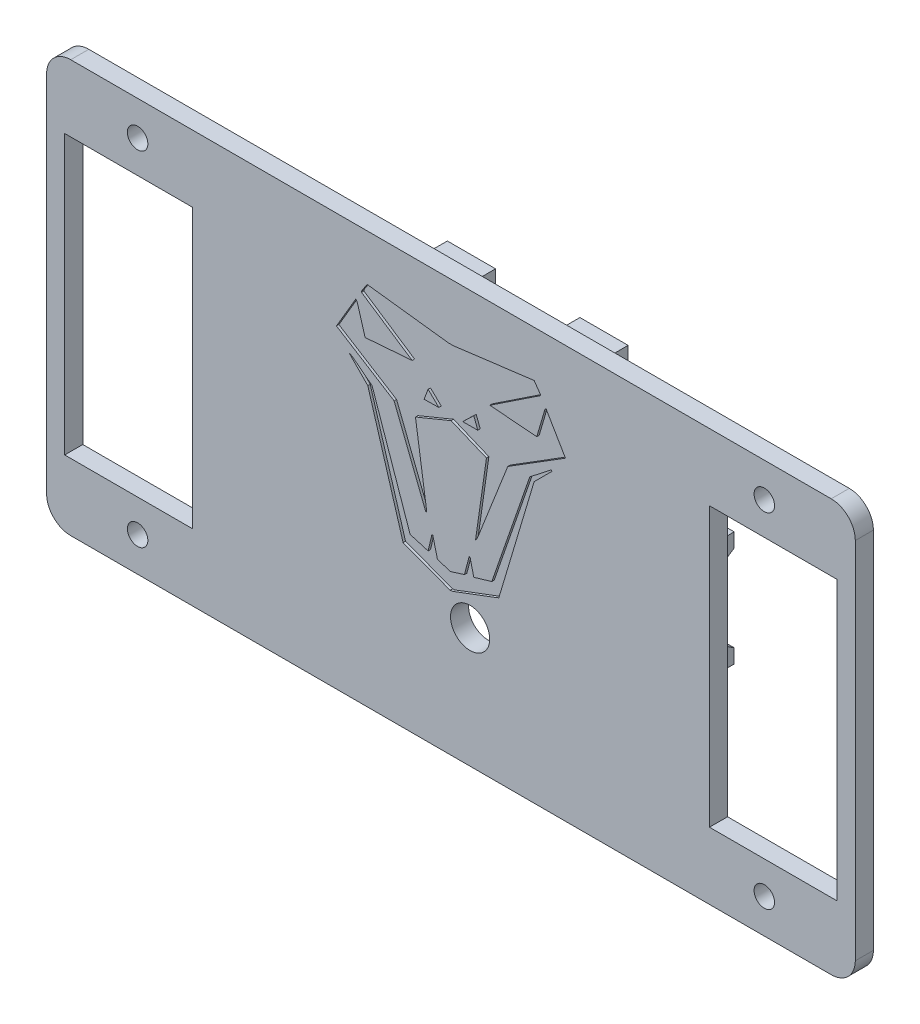
SolidWorks part; units mm, degrees
material "Overture Super PLA Plus"
ref_plane "Front Plane" through (0, 0, 0) normal (0, 0, 1) x (1, 0, 0)
ref_plane "Top Plane" through (0, 0, 0) normal (0, 1, 0) x (1, 0, 0)
ref_plane "Right Plane" through (0, 0, 0) normal (1, 0, 0) x (0, 0, -1)
sketch "Lid_Footprint" plane through (0, 0, 0) normal (0, 0, 1) x (1, 0, 0)
  line L1 (-67.1, -34.2) -> (67.1, -34.2)
  line L2 (-67.1, -34.2) -> (-67.1, 34.2)
  line L3 (-67.1, 34.2) -> (67.1, 34.2)
  line L4 (67.1, -34.2) -> (67.1, 34.2)
  dimension "R1_Width" = 134.2
  dimension "R1_Length" = 68.4
  dimension "R1_X" = 67.1
  dimension "R1_Y" = 34.2
extrude "Lid_Plate" add sketch "Lid_Footprint" along normal blind 3 from offset 32.5
sketch "Wheel_Well_Profile" plane through (0, 0, 0) normal (0, 0, 1) x (1, 0, 0)
  line L1 (42.9, -23.1) -> (64.1, -23.1)
  line L2 (42.9, -23.1) -> (42.9, 23.1)
  line L3 (42.9, 23.1) -> (64.1, 23.1)
  line L4 (64.1, -23.1) -> (64.1, 23.1)
  line L6 (-64.1, -23.1) -> (-42.9, -23.1)
  line L7 (-64.1, -23.1) -> (-64.1, 23.1)
  line L8 (-64.1, 23.1) -> (-42.9, 23.1)
  line L9 (-42.9, -23.1) -> (-42.9, 23.1)
  dimension "R1_Width" = 21.2
  dimension "R1_Length" = 46.2
  dimension "R1_X" = 42.9
  dimension "R1_Y" = 23.1
  dimension "R2_Width" = 21.2
  dimension "R2_Length" = 46.2
  dimension "R2_X" = 64.1
  dimension "R2_Y" = 23.1
extrude "Wheel_Clearance_Windows" cut sketch "Wheel_Well_Profile" against normal blind 5 from offset 36
sketch "Lid_Rib_Profile" plane through (0, 0, 0) normal (0, 0, 1) x (1, 0, 0)
  line L1 (-39, -8) -> (39, -8)
  line L2 (-39, -8) -> (-39, -5.5)
  line L3 (-39, -5.5) -> (39, -5.5)
  line L4 (39, -8) -> (39, -5.5)
  line L6 (-39, 5.5) -> (39, 5.5)
  line L7 (-39, 5.5) -> (-39, 8)
  line L8 (-39, 8) -> (39, 8)
  line L9 (39, 5.5) -> (39, 8)
  dimension "R1_Width" = 78
  dimension "R1_Length" = 2.5
  dimension "R1_X" = 39
  dimension "R1_Y" = 8
  dimension "R2_Width" = 78
  dimension "R2_Length" = 2.5
  dimension "R2_X" = 39
  dimension "R2_Y" = 5.5
extrude "Lid_Stiffening_Ribs" add sketch "Lid_Rib_Profile" along normal blind 3 from offset 29.5
sketch "Upper_Motor_Clamp_Profile" plane through (0, 0, 0) normal (0, 0, 1) x (1, 0, 0)
  line L1 (-35.1, -9.5) -> (-25.1, -9.5)
  line L2 (-35.1, -9.5) -> (-35.1, 9.5)
  line L3 (-35.1, 9.5) -> (-25.1, 9.5)
  line L4 (-25.1, -9.5) -> (-25.1, 9.5)
  line L6 (25.1, -9.5) -> (35.1, -9.5)
  line L7 (25.1, -9.5) -> (25.1, 9.5)
  line L8 (25.1, 9.5) -> (35.1, 9.5)
  line L9 (35.1, -9.5) -> (35.1, 9.5)
  dimension "R1_Width" = 10
  dimension "R1_Length" = 19
  dimension "R1_X" = 35.1
  dimension "R1_Y" = 9.5
  dimension "R2_Width" = 10
  dimension "R2_Length" = 19
  dimension "R2_X" = 25.1
  dimension "R2_Y" = 9.5
extrude "Lid_Motor_Clamp_Blocks" add sketch "Upper_Motor_Clamp_Profile" along normal blind 8.9 from offset 23.6
sketch "Upper_Clamp_Radius_Profile" plane through (0, 0, 0) normal (1, 0, 0) x (0, 0, -1)
  circle A0 centre (-19.6, 0) radius 8.2
  dimension "C1_Diameter" = 16.4
  dimension "Motor_Axis_Height" = 19.6
extrude "Upper_Motor_Clamp_Seats_R8p2" cut sketch "Upper_Clamp_Radius_Profile" against normal blind 72 from offset 36
sketch "Lid_Registration_Profile" plane through (0, 0, 0) normal (0, 0, 1) x (1, 0, 0)
  line L1 (-32.5, 30) -> (-0.5, 30)
  line L2 (-32.5, 30) -> (-32.5, 30.9)
  line L3 (-32.5, 30.9) -> (-0.5, 30.9)
  line L4 (-0.5, 30) -> (-0.5, 30.9)
  line L6 (0.5, 30) -> (32.5, 30)
  line L7 (0.5, 30) -> (0.5, 30.9)
  line L8 (0.5, 30.9) -> (32.5, 30.9)
  line L9 (32.5, 30) -> (32.5, 30.9)
  line L11 (-32.5, -30.9) -> (-0.5, -30.9)
  line L12 (-32.5, -30.9) -> (-32.5, -30)
  line L13 (-32.5, -30) -> (-0.5, -30)
  line L14 (-0.5, -30.9) -> (-0.5, -30)
  line L16 (0.5, -30.9) -> (32.5, -30.9)
  line L17 (0.5, -30.9) -> (0.5, -30)
  line L18 (0.5, -30) -> (32.5, -30)
  line L19 (32.5, -30.9) -> (32.5, -30)
  dimension "R1_Width" = 32
  dimension "R1_Length" = 0.9
  dimension "R1_X" = 32.5
  dimension "R1_Y" = 30
  dimension "R2_Width" = 32
  dimension "R2_Length" = 0.9
  dimension "R2_X" = 0.5
  dimension "R2_Y" = 30
  dimension "R3_Width" = 32
  dimension "R3_Length" = 0.9
  dimension "R3_X" = 32.5
  dimension "R3_Y" = 30.9
  dimension "R4_Width" = 32
  dimension "R4_Length" = 0.9
  dimension "R4_X" = 0.5
  dimension "R4_Y" = 30.9
extrude "Registration_Tabs" add sketch "Lid_Registration_Profile" along normal blind 1.5 from offset 31
sketch "Battery_Upper_Stop_Profile" plane through (0, 0, 0) normal (0, 0, 1) x (1, 0, 0)
  line L1 (-15, 17) -> (-7, 17)
  line L2 (-15, 17) -> (-15, 25)
  line L3 (-15, 25) -> (-7, 25)
  line L4 (-7, 17) -> (-7, 25)
  line L6 (7, 17) -> (15, 17)
  line L7 (7, 17) -> (7, 25)
  line L8 (7, 25) -> (15, 25)
  line L9 (15, 17) -> (15, 25)
  dimension "R1_Width" = 8
  dimension "R1_Length" = 8
  dimension "R1_X" = 15
  dimension "R1_Y" = 17
  dimension "R2_Width" = 8
  dimension "R2_Length" = 8
  dimension "R2_X" = 7
  dimension "R2_Y" = 17
extrude "Battery_Soft_Pad_Stops" add sketch "Battery_Upper_Stop_Profile" along normal blind 11.4 from offset 21.1
sketch "Lid_M3_Clearance_Profile" plane through (0, 0, 0) normal (0, 0, 1) x (1, 0, 0)
  circle A0 centre (-52, -28.5) radius 1.7
  circle A1 centre (-52, 28.5) radius 1.7
  circle A2 centre (52, -28.5) radius 1.7
  circle A3 centre (52, 28.5) radius 1.7
  dimension "C1_Diameter" = 3.4
  dimension "C2_Diameter" = 3.4
  dimension "C3_Diameter" = 3.4
  dimension "C4_Diameter" = 3.4
extrude "Lid_M3_Clearance_Holes" cut sketch "Lid_M3_Clearance_Profile" against normal blind 5 from offset 36
sketch "Switch_Retention_Rail_Profile" plane through (0, 0, 0) normal (0, 0, 1) x (1, 0, 0)
  line L1 (-11.5, -18.5) -> (-9.8, -18.5)
  line L2 (-11.5, -18.5) -> (-11.5, -10.2)
  line L3 (-11.5, -10.2) -> (-9.8, -10.2)
  line L4 (-9.8, -18.5) -> (-9.8, -10.2)
  line L6 (9.8, -18.5) -> (11.5, -18.5)
  line L7 (9.8, -18.5) -> (9.8, -10.2)
  line L8 (9.8, -10.2) -> (11.5, -10.2)
  line L9 (11.5, -18.5) -> (11.5, -10.2)
  dimension "R1_Width" = 1.7
  dimension "R1_Length" = 8.3
  dimension "R1_X" = 11.5
  dimension "R1_Y" = 18.5
  dimension "R2_Width" = 1.7
  dimension "R2_Length" = 8.3
  dimension "R2_X" = 9.8
  dimension "R2_Y" = 18.5
extrude "Switch_Retention_Rails" add sketch "Switch_Retention_Rail_Profile" along normal blind 14.1 from offset 18.4
sketch "Switch_Retention_Ledge_Profile" plane through (0, 0, 0) normal (0, 0, 1) x (1, 0, 0)
  line L1 (-11.5, -18.5) -> (-8.8, -18.5)
  line L2 (-11.5, -18.5) -> (-11.5, -10.2)
  line L3 (-11.5, -10.2) -> (-8.8, -10.2)
  line L4 (-8.8, -18.5) -> (-8.8, -10.2)
  line L6 (8.8, -18.5) -> (11.5, -18.5)
  line L7 (8.8, -18.5) -> (8.8, -10.2)
  line L8 (8.8, -10.2) -> (11.5, -10.2)
  line L9 (11.5, -18.5) -> (11.5, -10.2)
  dimension "R1_Width" = 2.7
  dimension "R1_Length" = 8.3
  dimension "R1_X" = 11.5
  dimension "R1_Y" = 18.5
  dimension "R2_Width" = 2.7
  dimension "R2_Length" = 8.3
  dimension "R2_X" = 8.8
  dimension "R2_Y" = 18.5
extrude "Switch_Retention_Ledges" add sketch "Switch_Retention_Ledge_Profile" along normal blind 1 from offset 17.4
sketch "Switch_Tool_Access_Profile" plane through (0, 0, 0) normal (0, 0, 1) x (1, 0, 0)
  circle A0 centre (3.175, -14.325) radius 3.25
  dimension "C1_Diameter" = 6.5
extrude "Switch_Tool_Access" cut sketch "Switch_Tool_Access_Profile" against normal blind 5 from offset 36
fillet "Lid_Outer_Corners_R4" radius 4 4 edges at (-67.1, 34.2, 34) (67.1, 34.2, 34) (67.1, -34.2, 34) (-67.1, -34.2, 34)
sketch "Snake_Logo_Native_Profile" plane through (0, 0, 0) normal (0, 0, 1) x (1, 0, 0)
  line L0 (13.8006, 26.5575) -> (14.8515, 25.064)
  line L1 (14.8515, 25.064) -> (14.8515, 24.8981)
  line L2 (14.8515, 24.8981) -> (6.444, 19.3115)
  line L3 (6.444, 19.3115) -> (14.2431, 18.7031)
  line L4 (14.2431, 18.7031) -> (15.46, 22.8515)
  line L5 (15.46, 22.8515) -> (15.6259, 23.3493)
  line L6 (15.6259, 23.3493) -> (15.7918, 23.46)
  line L7 (15.7918, 23.46) -> (19, 17.984)
  line L8 (19, 17.984) -> (9.4309, 12.0102)
  line L9 (9.4309, 12.0102) -> (4.3974, -0.7671)
  line L10 (4.3974, -0.7671) -> (4.0655, -1.3202)
  line L11 (4.0655, -1.3202) -> (5.8908, 11.4571)
  line L12 (5.8908, 11.4571) -> (0.0277, 13.8908)
  line L13 (0.0277, 13.8908) -> (-5.8908, 11.4571)
  line L14 (-5.8908, 11.4571) -> (-4.0655, -0.8777)
  line L15 (-4.0655, -0.8777) -> (-4.0655, -1.2649)
  line L16 (-4.0655, -1.2649) -> (-4.1761, -1.3202)
  line L17 (-4.1761, -1.3202) -> (-9.4309, 12.0102)
  line L18 (-9.4309, 12.0102) -> (-19, 17.984)
  line L19 (-19, 17.984) -> (-15.7918, 23.46)
  line L20 (-15.7918, 23.46) -> (-15.5706, 23.1834)
  line L21 (-15.5706, 23.1834) -> (-14.2431, 18.7031)
  line L22 (-14.2431, 18.7031) -> (-6.444, 19.3115)
  line L23 (-6.444, 19.3115) -> (-14.8515, 24.8981)
  line L24 (-14.8515, 24.8981) -> (-14.8515, 25.064)
  line L25 (-14.8515, 25.064) -> (-13.9112, 26.5022)
  line L26 (-13.9112, 26.5022) -> (-0.4148, 24.8428)
  line L27 (-0.4148, 24.8428) -> (0.4148, 24.8428)
  line L28 (0.4148, 24.8428) -> (13.8006, 26.5575)
  line L29 (-16.8428, 15.1077) -> (-16.5662, 15.0524)
  line L30 (-16.5662, 15.0524) -> (-16.6215, 14.9418)
  line L31 (-16.6215, 14.9418) -> (-16.5109, 14.9971)
  line L32 (-16.5109, 14.9971) -> (-15.9025, 14.5546)
  line L33 (-15.9025, 14.5546) -> (-13.1368, 12.3974)
  line L34 (-13.1368, 12.3974) -> (-13.0262, 12.1761)
  line L35 (-13.0262, 12.1761) -> (-6.7758, -5.8559)
  line L36 (-6.7758, -5.8559) -> (-3.7889, -6.7409)
  line L37 (-3.7889, -6.7409) -> (-3.1805, -4.1412)
  line L38 (-3.1805, -4.1412) -> (-3.0146, -4.0859)
  line L39 (-3.0146, -4.0859) -> (-2.2402, -7.1834)
  line L40 (-2.2402, -7.1834) -> (-0.083, -7.8472)
  line L41 (-0.083, -7.8472) -> (2.2402, -7.1281)
  line L42 (2.2402, -7.1281) -> (3.0146, -4.1412)
  line L43 (3.0146, -4.1412) -> (3.1805, -4.1965)
  line L44 (3.1805, -4.1965) -> (3.7889, -6.7409)
  line L45 (3.7889, -6.7409) -> (6.7758, -5.8559)
  line L46 (6.7758, -5.8559) -> (13.0815, 12.3421)
  line L47 (13.0815, 12.3421) -> (16.6215, 15.1077)
  line L48 (16.6215, 15.1077) -> (16.7875, 14.9971)
  line L49 (16.7875, 14.9971) -> (13.8006, 12.0102)
  line L50 (13.8006, 12.0102) -> (7.9374, -7.6259)
  line L51 (7.9374, -7.6259) -> (0.3042, -10.5022)
  line L52 (0.3042, -10.5022) -> (-0.1383, -10.5575)
  line L53 (-0.1383, -10.5575) -> (-7.9374, -7.6259)
  line L54 (-7.9374, -7.6259) -> (-13.8006, 12.0102)
  line L55 (-13.8006, 12.0102) -> (-16.8428, 15.1077)
  line L56 (-4.4527, 14.7205) -> (-2.0189, 14.7758)
  line L57 (-2.0189, 14.7758) -> (-3.7889, 16.4905)
  line L58 (-3.7889, 16.4905) -> (-4.4527, 14.7205)
  line L59 (1.9636, 14.7205) -> (4.4527, 14.7205)
  line L60 (4.4527, 14.7205) -> (3.7889, 16.4905)
  line L61 (3.7889, 16.4905) -> (1.9636, 14.7205)
extrude "Snake_Logo_Engraved" cut sketch "Snake_Logo_Native_Profile" against normal blind 0.4 from offset 35.5
equation "\"Overall_Width\"= 134.2mm"
equation "\"Overall_Length\"= 68.4mm"
equation "\"Wall\"= 3mm"
equation "\"Floor\"= 2.6mm"
equation "\"Case_Height\"= 32.5mm"
equation "\"Lid_Thickness\"= 3mm"
equation "\"Wheel_Diameter\"= 43.2mm"
equation "\"Wheel_Width\"= 14mm"
equation "\"Wheel_Bay_Inner_X\"= 42.9mm"
equation "\"Wheel_Radial_Clearance\"= 1.5mm"
equation "\"Wheel_Bay_Half_Length\"= \"Wheel_Diameter\"/2+\"Wheel_Radial_Clearance\""
equation "\"Ground_Clearance\"= 2mm"
equation "\"Motor_Axis_Z\"= \"Wheel_Diameter\"/2-\"Ground_Clearance\""
equation "\"Motor_Face_X\"= 38.1mm"
equation "\"Motor_Clamp_Radius\"= 8.2mm"
equation "\"Screw_Clearance\"= 3.4mm"
equation "\"Nut_AF_Clearance\"= 5.7mm"
equation "\"Engraving_Depth\"= 0.4mm"
equation "\"Hub_Offset_Min_Allowed\"= \"Wheel_Bay_Inner_X\"+1mm-\"Motor_Face_X\""
equation "\"Hub_Offset_Max_Allowed\"= \"Overall_Width\"/2-\"Wall\"-1mm-\"Wheel_Width\"-\"Motor_Face_X\""
equation "\"R1_Width@Lid_Footprint\" = \"Overall_Width\""
equation "\"R1_Length@Lid_Footprint\" = \"Overall_Length\""
equation "\"R1_X@Lid_Footprint\" = \"Overall_Width\"/2"
equation "\"R1_Y@Lid_Footprint\" = \"Overall_Length\"/2"
equation "\"D1@Lid_Plate\" = \"Lid_Thickness\""
equation "\"R1_Width@Wheel_Well_Profile\" = \"Overall_Width\"/2-\"Wall\"-\"Wheel_Bay_Inner_X\""
equation "\"R1_Length@Wheel_Well_Profile\" = 2*\"Wheel_Bay_Half_Length\""
equation "\"R1_X@Wheel_Well_Profile\" = \"Wheel_Bay_Inner_X\""
equation "\"R1_Y@Wheel_Well_Profile\" = \"Wheel_Bay_Half_Length\""
equation "\"R2_Width@Wheel_Well_Profile\" = \"Overall_Width\"/2-\"Wall\"-\"Wheel_Bay_Inner_X\""
equation "\"R2_Length@Wheel_Well_Profile\" = 2*\"Wheel_Bay_Half_Length\""
equation "\"R2_X@Wheel_Well_Profile\" = \"Overall_Width\"/2-\"Wall\""
equation "\"R2_Y@Wheel_Well_Profile\" = \"Wheel_Bay_Half_Length\""
equation "\"C1_Diameter@Upper_Clamp_Radius_Profile\" = 2*\"Motor_Clamp_Radius\""
equation "\"C1_Diameter@Lid_M3_Clearance_Profile\" = \"Screw_Clearance\""
equation "\"C2_Diameter@Lid_M3_Clearance_Profile\" = \"Screw_Clearance\""
equation "\"C3_Diameter@Lid_M3_Clearance_Profile\" = \"Screw_Clearance\""
equation "\"C4_Diameter@Lid_M3_Clearance_Profile\" = \"Screw_Clearance\""
equation "\"Motor_Axis_Height@Upper_Clamp_Radius_Profile\" = \"Motor_Axis_Z\""
equation "\"D19@Lid_Motor_Clamp_Blocks\" = \"Motor_Axis_Z\"+4mm"
equation "\"D1@Lid_Motor_Clamp_Blocks\" = \"Case_Height\"-\"Motor_Axis_Z\"-4mm"
equation "\"D19@Lid_Plate\" = \"Case_Height\""
equation "\"D1@Snake_Logo_Engraved\" = \"Engraving_Depth\""
